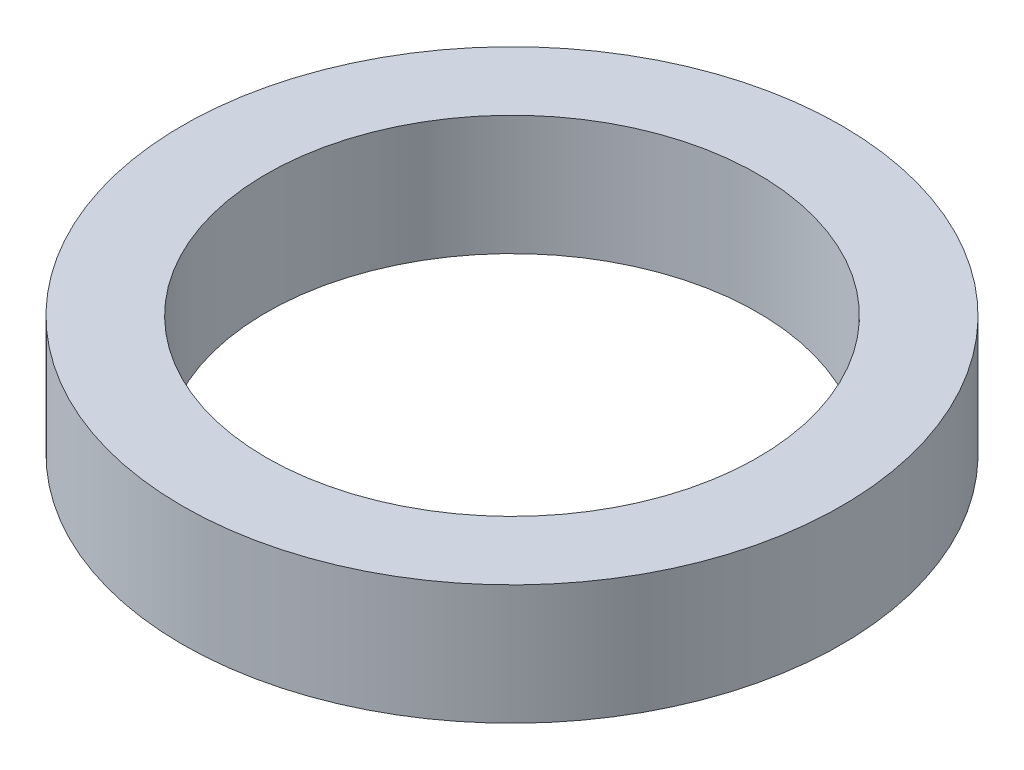
SolidWorks part; units mm, degrees
ref_plane "Front Plane" through (0, 0, 0) normal (0, 0, 1) x (1, 0, 0)
ref_plane "Top Plane" through (0, 0, 0) normal (0, 1, 0) x (1, 0, 0)
ref_plane "Right Plane" through (0, 0, 0) normal (1, 0, 0) x (0, 0, -1)
sketch "Sketch1" plane through (0, 0, 0) normal (0, 1, 0) x (1, 0, 0)
  circle A0 centre (0, 0) radius 2.05
  circle A1 centre (0, 0) radius 2.75
  dimension "D1" = 4.1
  dimension "D2" = 5.5
extrude "Boss-Extrude1" add sketch "Sketch1" along normal blind 1
